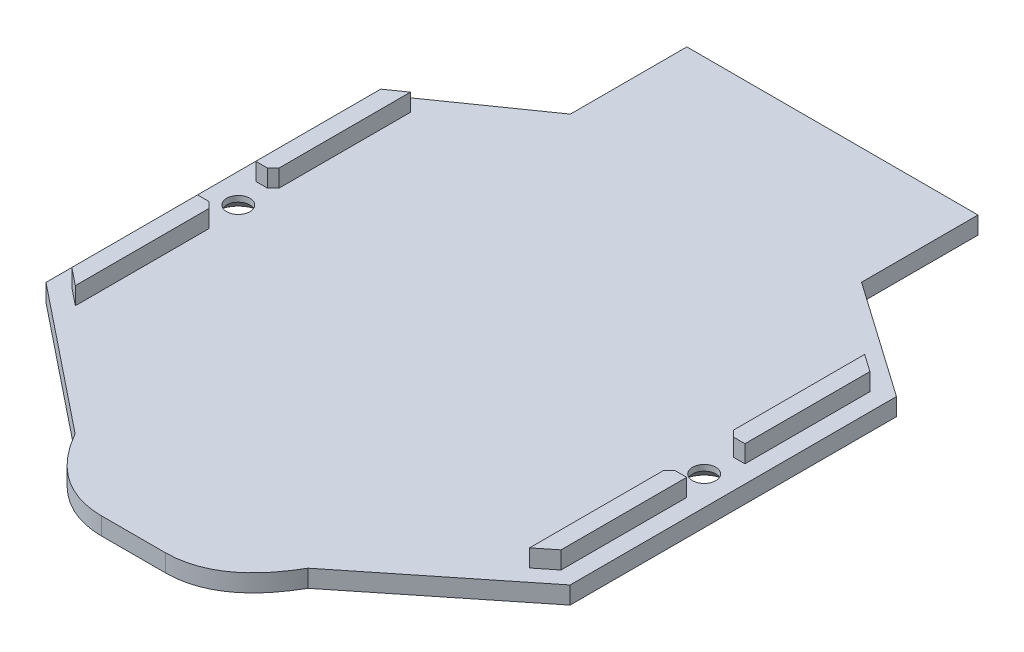
SolidWorks part; units mm, degrees
ref_plane "Front Plane" through (0, 0, 0) normal (0, 0, 1) x (1, 0, 0)
ref_plane "Top Plane" through (0, 0, 0) normal (0, 1, 0) x (1, 0, 0)
ref_plane "Right Plane" through (0, 0, 0) normal (1, 0, 0) x (0, 0, -1)
sketch "Sketch1" plane through (0, 0, 0) normal (0, 1, 0) x (1, 0, 0)
  line L0 (16.2204, 37.1807) -> (14.3154, 37.1807)
  line L1 (14.3154, 37.1807) -> (14.3154, 23.4889)
  line L2 (14.3154, 23.4889) -> (27.0154, 14.5989)
  line L3 (27.0154, 14.5989) -> (27.0154, 0.9716)
  line L4 (27.0154, 0.9716) -> (25.7454, 0.9716)
  line L5 (25.7454, -5.3784) -> (27.0154, -5.3784)
  line L6 (27.0154, -5.3784) -> (27.0154, -19.0819)
  line L7 (27.0154, -19.0819) -> (11.5652, -31.4422)
  line L8 (3.8247, -37.1143) -> (-3.1264, -37.1143)
  line L9 (-10.8743, -31.4422) -> (-26.3246, -19.0819)
  line L10 (-26.3246, -19.0819) -> (-26.3246, -5.3784)
  line L11 (-26.3246, -5.3784) -> (-25.0546, -5.3784)
  line L12 (-25.0546, 0.9716) -> (-26.3246, 0.9716)
  line L13 (-26.3246, 0.9716) -> (-26.3246, 14.5989)
  line L14 (-26.3246, 14.5989) -> (-13.6246, 23.4889)
  line L15 (-13.6246, 23.4889) -> (-13.6246, 37.1807)
  line L16 (-13.6246, 37.1807) -> (-15.5296, 37.1807)
  line L17 (-15.5296, 37.1807) -> (-15.5296, 24.4807)
  line L18 (-15.5296, 24.4807) -> (-28.2296, 15.5907)
  line L19 (-28.2296, 15.5907) -> (-28.2296, -19.9975)
  line L20 (-28.2296, -19.9975) -> (-12.3546, -32.6975)
  line L21 (-3.1338, -39.0193) -> (3.8247, -39.0193)
  line L22 (13.0454, -32.6975) -> (28.9204, -19.9975)
  line L23 (28.9204, -19.9975) -> (28.9204, 15.5907)
  line L24 (28.9204, 15.5907) -> (16.2204, 24.4807)
  line L25 (16.2204, 24.4807) -> (16.2204, 37.1807)
  line L26 (-15.5296, 37.1807) -> (16.2204, 37.1807)
  arc A0 (25.7454, 0.9716) -> (25.7454, -5.3784) centre (25.7454, -2.2034) ccw
  arc A1 (-25.0546, -5.3784) -> (-25.0546, 0.9716) centre (-25.0546, -2.2034) ccw
  spline S0 degree 3 poles (11.5652, -31.4422) (11.1586, -32.1832) (10.712, -32.8933) (9.9543, -33.8908) (9.687, -34.2118) (9.1149, -34.8251) (8.8087, -35.1186) (8.1538, -35.6622) (7.8103, -35.908) (7.267, -36.2313) (7.0812, -36.3315) (6.6996, -36.5157) (6.5025, -36.5999) (5.5058, -36.9719) (4.6781, -37.1102) (3.8247, -37.1143) knots 0 0 0 0 0.25 0.25 0.375 0.375 0.5 0.5 0.625 0.625 0.6875 0.6875 0.75 0.75 1 1 1 1
  spline S1 degree 3 poles (-3.1264, -37.1143) (-3.9804, -37.111) (-4.8089, -36.9733) (-5.8065, -36.602) (-6.0037, -36.5178) (-6.3858, -36.3339) (-6.5718, -36.2337) (-7.1158, -35.9104) (-7.4596, -35.6646) (-8.1153, -35.121) (-8.4218, -34.8273) (-8.9945, -34.2137) (-9.2621, -33.8925) (-10.0205, -32.8944) (-10.4674, -32.1837) (-10.8743, -31.4422) knots 0 0 0 0 0.25 0.25 0.3125 0.3125 0.375 0.375 0.5 0.5 0.625 0.625 0.75 0.75 1 1 1 1
  spline S2 degree 3 poles (-12.3546, -32.6975) (-10.3573, -36.1919) (-7.4671, -39.0025) (-3.1338, -39.0193) knots 0.450644 0.450644 0.450644 0.450644 1 1 1 1
  spline S3 degree 3 poles (3.8247, -39.0193) (8.158, -39.0025) (11.0482, -36.1919) (13.0454, -32.6975) knots 0.450644 0.450644 0.450644 0.450644 1 1 1 1
sketch "Sketch2" plane through (0, 0, 0) normal (0, 1, 0) x (1, 0, 0)
  line L0 (-28.2296, 15.5907) -> (-28.2296, -19.9975) construction
  line L1 (-15.5296, 24.4807) -> (-28.2296, 15.5907) construction
  line L2 (-15.5296, 37.1807) -> (-15.5296, 24.4807) construction
  line L3 (-15.5296, 37.1807) -> (16.2204, 37.1807) construction
  line L4 (16.2204, 24.4807) -> (16.2204, 37.1807) construction
  line L5 (28.9204, 15.5907) -> (16.2204, 24.4807) construction
  line L6 (28.9204, -19.9975) -> (28.9204, 15.5907) construction
  line L7 (13.0454, -32.6975) -> (28.9204, -19.9975) construction
  line L8 (-3.1338, -39.0193) -> (3.8247, -39.0193) construction
  line L9 (-28.2296, -19.9975) -> (-12.3546, -32.6975) construction
  line L10 (-28.2296, 15.5907) -> (-28.2296, -19.9975)
  line L11 (-15.5296, 24.4807) -> (-28.2296, 15.5907)
  line L12 (-15.5296, 37.1807) -> (-15.5296, 24.4807)
  line L13 (-15.5296, 37.1807) -> (16.2204, 37.1807)
  line L14 (16.2204, 24.4807) -> (16.2204, 37.1807)
  line L15 (28.9204, 15.5907) -> (16.2204, 24.4807)
  line L16 (28.9204, -19.9975) -> (28.9204, 15.5907)
  line L17 (13.0454, -32.6975) -> (28.9204, -19.9975)
  line L18 (-3.1338, -39.0193) -> (3.8247, -39.0193)
  line L19 (-28.2296, -19.9975) -> (-12.3546, -32.6975)
  spline S0 degree 3 poles (-1372.2239, 3712.8512) (1134.3547, -4013.4655) (-902.3208, 4019.2005) (797.1704, -3954.7495) knots -5.551331 -5.551331 -5.551331 -5.551331 8.013046 8.013046 8.013046 8.013046 only from (3.8247, -39.0193) to (13.0454, -32.6975) construction
  spline S1 degree 3 poles (-601.8963, -3989.0758) (204.2826, 518.7984) (43.0145, -54.773) (-5.8065, -36.602) (-6.0037, -36.5178) (-6.3858, -36.3339) (-6.5718, -36.2337) (-7.1158, -35.9104) (-7.4596, -35.6646) (-8.1153, -35.121) (-8.4218, -34.8273) (-8.9945, -34.2137) (-9.2621, -33.8925) (-39.1665, 5.4647) (132.9955, 200.2639) (-3261.6051, -2358.0304) knots -14.980553 -14.980553 -14.980553 -14.980553 0.25 0.25 0.3125 0.3125 0.375 0.375 0.5 0.5 0.625 0.625 0.75 0.75 15.412318 15.412318 15.412318 15.412318 only from (-3.1264, -37.1143) to (-10.8743, -31.4422) construction
  spline S2 degree 3 poles (-796.4893, -3954.7951) (903.0253, 4019.2584) (-1133.6825, -4013.5351) (1372.9405, 3712.9303) knots -6.562429 -6.562429 -6.562429 -6.562429 7.002021 7.002021 7.002021 7.002021 only from (-12.3546, -32.6975) to (-3.1338, -39.0193) construction
  spline S3 degree 3 poles (3.8247, -39.0193) (8.158, -39.0025) (11.0482, -36.1919) (13.0454, -32.6975) knots 0.450644 0.450644 0.450644 0.450644 1 1 1 1
  spline S4 degree 3 poles (-3.1264, -37.1143) (-3.9804, -37.111) (-4.8089, -36.9733) (-5.8065, -36.602) (-6.0037, -36.5178) (-6.3858, -36.3339) (-6.5718, -36.2337) (-7.1158, -35.9104) (-7.4596, -35.6646) (-8.1153, -35.121) (-8.4218, -34.8273) (-8.9945, -34.2137) (-9.2621, -33.8925) (-10.0205, -32.8944) (-10.4674, -32.1837) (-10.8743, -31.4422) knots 0 0 0 0 0.25 0.25 0.3125 0.3125 0.375 0.375 0.5 0.5 0.625 0.625 0.75 0.75 1 1 1 1
  spline S5 degree 3 poles (-12.3546, -32.6975) (-10.3573, -36.1919) (-7.4671, -39.0025) (-3.1338, -39.0193) knots 0.450644 0.450644 0.450644 0.450644 1 1 1 1
extrude "Boss-Extrude1" add sketch "Sketch2" along normal blind 1.905
sketch "Sketch3" plane through (0, 0, 0) normal (0, 1, 0) x (1, 0, 0)
  line L0 (-13.6246, 37.1807) -> (-15.5296, 37.1807) construction
  line L1 (-13.6246, 23.4889) -> (-13.6246, 37.1807) construction
  line L2 (-26.3246, 14.5989) -> (-13.6246, 23.4889) construction
  line L3 (-26.3246, 0.9716) -> (-26.3246, 14.5989) construction
  line L4 (-25.0546, 0.9716) -> (-26.3246, 0.9716) construction
  line L5 (-26.3246, -5.3784) -> (-25.0546, -5.3784) construction
  line L6 (-26.3246, -19.0819) -> (-26.3246, -5.3784) construction
  line L7 (-10.8743, -31.4422) -> (-26.3246, -19.0819) construction
  line L8 (3.8247, -37.1143) -> (-3.1264, -37.1143) construction
  line L9 (27.0154, -19.0819) -> (11.5652, -31.4422) construction
  line L10 (27.0154, -5.3784) -> (27.0154, -19.0819) construction
  line L11 (25.7454, -5.3784) -> (27.0154, -5.3784) construction
  line L12 (27.0154, 0.9716) -> (25.7454, 0.9716) construction
  line L13 (27.0154, 14.5989) -> (27.0154, 0.9716) construction
  line L14 (14.3154, 23.4889) -> (27.0154, 14.5989) construction
  line L15 (14.3154, 37.1807) -> (14.3154, 23.4889) construction
  line L16 (16.2204, 37.1807) -> (14.3154, 37.1807) construction
  line L17 (-15.5296, 37.1807) -> (-15.5296, 24.4807) construction
  line L18 (-15.5296, 24.4807) -> (-28.2296, 15.5907) construction
  line L19 (-28.2296, 15.5907) -> (-28.2296, -19.9975) construction
  line L20 (-28.2296, -19.9975) -> (-12.3546, -32.6975) construction
  line L21 (-3.1338, -39.0193) -> (3.8247, -39.0193) construction
  line L22 (13.0454, -32.6975) -> (28.9204, -19.9975) construction
  line L23 (28.9204, -19.9975) -> (28.9204, 15.5907) construction
  line L24 (28.9204, 15.5907) -> (16.2204, 24.4807) construction
  line L25 (16.2204, 24.4807) -> (16.2204, 37.1807) construction
  line L26 (-15.5296, 37.1807) -> (16.2204, 37.1807) construction
  line L27 (-13.6246, 37.1807) -> (-15.5296, 37.1807)
  line L28 (-13.6246, 23.4889) -> (-13.6246, 37.1807)
  line L29 (-26.3246, 14.5989) -> (-13.6246, 23.4889)
  line L30 (-26.3246, 0.9716) -> (-26.3246, 14.5989)
  line L31 (-25.0546, 0.9716) -> (-26.3246, 0.9716)
  line L32 (-26.3246, -5.3784) -> (-25.0546, -5.3784)
  line L33 (-26.3246, -19.0819) -> (-26.3246, -5.3784)
  line L34 (-10.8743, -31.4422) -> (-26.3246, -19.0819)
  line L35 (3.8247, -37.1143) -> (-3.1264, -37.1143)
  line L36 (27.0154, -19.0819) -> (11.5652, -31.4422)
  line L37 (27.0154, -5.3784) -> (27.0154, -19.0819)
  line L38 (25.7454, -5.3784) -> (27.0154, -5.3784)
  line L39 (27.0154, 0.9716) -> (25.7454, 0.9716)
  line L40 (27.0154, 14.5989) -> (27.0154, 0.9716)
  line L41 (14.3154, 23.4889) -> (27.0154, 14.5989)
  line L42 (14.3154, 37.1807) -> (14.3154, 23.4889)
  line L43 (16.2204, 37.1807) -> (14.3154, 37.1807)
  line L44 (-15.5296, 37.1807) -> (-15.5296, 24.4807)
  line L45 (-15.5296, 24.4807) -> (-28.2296, 15.5907)
  line L46 (-28.2296, 15.5907) -> (-28.2296, -19.9975)
  line L47 (-28.2296, -19.9975) -> (-12.3546, -32.6975)
  line L48 (-3.1338, -39.0193) -> (3.8247, -39.0193)
  line L49 (13.0454, -32.6975) -> (28.9204, -19.9975)
  line L50 (28.9204, -19.9975) -> (28.9204, 15.5907)
  line L51 (28.9204, 15.5907) -> (16.2204, 24.4807)
  line L52 (16.2204, 24.4807) -> (16.2204, 37.1807)
  line L53 (-15.5296, 37.1807) -> (16.2204, 37.1807)
  line L54 (-25.0546, 0.9716) -> (-24.4196, 1.6066)
  line L55 (-24.4196, 1.6066) -> (-24.4196, 15.9324)
  line L56 (-25.0546, -5.3784) -> (-24.4196, -6.0134)
  line L57 (-24.4196, -6.0134) -> (-24.4196, -20.6059)
  line L58 (0.3454, 37.1807) -> (0.3454, -39.0193) construction
  line L59 (25.1104, -6.0134) -> (25.1104, -20.6059)
  line L60 (25.7454, -5.3784) -> (25.1104, -6.0134)
  line L61 (25.1104, 1.6066) -> (25.1104, 15.9324)
  line L62 (25.7454, 0.9716) -> (25.1104, 1.6066)
  line L63 (28.9204, 15.5907) -> (28.9204, -19.9975)
  line L64 (16.2204, 24.4807) -> (28.9204, 15.5907)
  line L65 (27.0154, -19.0819) -> (27.0154, -5.3784)
  line L66 (27.0154, -5.3784) -> (25.7454, -5.3784)
  line L67 (25.7454, 0.9716) -> (27.0154, 0.9716)
  line L68 (27.0154, 0.9716) -> (27.0154, 14.5989)
  line L69 (27.0154, 14.5989) -> (14.3154, 23.4889)
  arc A0 (-25.0546, -5.3784) -> (-25.0546, 0.9716) centre (-25.0546, -2.2034) ccw construction
  arc A1 (25.7454, 0.9716) -> (25.7454, -5.3784) centre (25.7454, -2.2034) ccw construction
  arc A2 (-25.0546, -5.3784) -> (-25.0546, 0.9716) centre (-25.0546, -2.2034) ccw
  arc A3 (25.7454, 0.9716) -> (25.7454, -5.3784) centre (25.7454, -2.2034) ccw
  arc A4 (25.7454, -5.3784) -> (25.7454, 0.9716) centre (25.7454, -2.2034) cw
  spline S0 degree 3 poles (-426.9181, -3004.5813) (179.2751, 431.0709) (39.1367, -53.3297) (-5.8065, -36.602) (-6.0037, -36.5178) (-6.3858, -36.3339) (-6.5718, -36.2337) (-7.1158, -35.9104) (-7.4596, -35.6646) (-8.1153, -35.121) (-8.4218, -34.8273) (-8.9945, -34.2137) (-9.2621, -33.8925) (-36.616, 2.108) (104.8717, 167.9052) (-2462.4158, -1757.1324) knots -13.76583 -13.76583 -13.76583 -13.76583 0.25 0.25 0.3125 0.3125 0.375 0.375 0.5 0.5 0.625 0.625 0.75 0.75 14.151142 14.151142 14.151142 14.151142 only from (-3.1264, -37.1143) to (-10.8743, -31.4422) construction
  spline S1 degree 3 poles (2463.1832, -1757.169) (-104.1653, 167.9053) (37.3056, 2.1164) (9.9543, -33.8908) (9.687, -34.2118) (9.1149, -34.8251) (8.8087, -35.1186) (8.1538, -35.6622) (7.8103, -35.908) (7.267, -36.2313) (7.0812, -36.3315) (6.6996, -36.5157) (6.5025, -36.5999) (-38.502, -53.3933) (-179.2821, 432.5621) (428.9356, -3004.4043) knots -13.162322 -13.162322 -13.162322 -13.162322 0.25 0.25 0.375 0.375 0.5 0.5 0.625 0.625 0.6875 0.6875 0.75 0.75 14.797872 14.797872 14.797872 14.797872 only from (11.5652, -31.4422) to (3.8247, -37.1143) construction
  spline S2 degree 3 poles (-589.7865, -2976.415) (667.4627, 3033.8674) (-863.1992, -3037.4657) (1061.4, 2762.7226) knots -5.954611 -5.954611 -5.954611 -5.954611 6.391637 6.391637 6.391637 6.391637 only from (-12.3546, -32.6975) to (-3.1338, -39.0193) construction
  spline S3 degree 3 poles (-1060.6911, 2762.6682) (863.8771, -3037.4176) (-666.7625, 3033.8272) (590.4708, -2976.3833) knots -4.940954 -4.940954 -4.940954 -4.940954 7.405233 7.405233 7.405233 7.405233 only from (3.8247, -39.0193) to (13.0454, -32.6975) construction
  spline S4 degree 3 poles (-3.1264, -37.1143) (-3.9804, -37.111) (-4.8089, -36.9733) (-5.8065, -36.602) (-6.0037, -36.5178) (-6.3858, -36.3339) (-6.5718, -36.2337) (-7.1158, -35.9104) (-7.4596, -35.6646) (-8.1153, -35.121) (-8.4218, -34.8273) (-8.9945, -34.2137) (-9.2621, -33.8925) (-10.0205, -32.8944) (-10.4674, -32.1837) (-10.8743, -31.4422) knots 0 0 0 0 0.25 0.25 0.3125 0.3125 0.375 0.375 0.5 0.5 0.625 0.625 0.75 0.75 1 1 1 1
  spline S5 degree 3 poles (11.5652, -31.4422) (11.1586, -32.1832) (10.712, -32.8933) (9.9543, -33.8908) (9.687, -34.2118) (9.1149, -34.8251) (8.8087, -35.1186) (8.1538, -35.6622) (7.8103, -35.908) (7.267, -36.2313) (7.0812, -36.3315) (6.6996, -36.5157) (6.5025, -36.5999) (5.5058, -36.9719) (4.6781, -37.1102) (3.8247, -37.1143) knots 0 0 0 0 0.25 0.25 0.375 0.375 0.5 0.5 0.625 0.625 0.6875 0.6875 0.75 0.75 1 1 1 1
  spline S6 degree 3 poles (-12.3546, -32.6975) (-10.3573, -36.1919) (-7.4671, -39.0025) (-3.1338, -39.0193) knots 0.450644 0.450644 0.450644 0.450644 1 1 1 1
  spline S7 degree 3 poles (3.8247, -39.0193) (8.158, -39.0025) (11.0482, -36.1919) (13.0454, -32.6975) knots 0.450644 0.450644 0.450644 0.450644 1 1 1 1
  dimension "D1" = 135
  dimension "D2" = 135
  dimension "D3" = 1.905
  dimension "D4" = 1.905
extrude "Boss-Extrude2" add sketch "Sketch3" along normal blind 3.81 contours L54 L55 L29 L30 L31 | L57 L56 L32 L33 L34 | L62 L39 L40 L41 L61 | L38 L60 L59 L36 L37
sketch "Sketch4" plane through (0, 0, 0) normal (0, 1, 0) x (1, 0, 0)
  line L0 (-13.6246, 37.1807) -> (-15.5296, 37.1807) construction
  line L1 (-13.6246, 23.4889) -> (-13.6246, 37.1807) construction
  line L2 (-26.3246, 14.5989) -> (-13.6246, 23.4889) construction
  line L3 (-26.3246, 0.9716) -> (-26.3246, 14.5989) construction
  line L4 (-25.0546, 0.9716) -> (-26.3246, 0.9716) construction
  line L5 (-26.3246, -5.3784) -> (-25.0546, -5.3784) construction
  line L6 (-26.3246, -19.0819) -> (-26.3246, -5.3784) construction
  line L7 (-10.8743, -31.4422) -> (-26.3246, -19.0819) construction
  line L8 (3.8247, -37.1143) -> (-3.1264, -37.1143) construction
  line L9 (27.0154, -19.0819) -> (11.5652, -31.4422) construction
  line L10 (27.0154, -5.3784) -> (27.0154, -19.0819) construction
  line L11 (25.7454, -5.3784) -> (27.0154, -5.3784) construction
  line L12 (27.0154, 0.9716) -> (25.7454, 0.9716) construction
  line L13 (27.0154, 14.5989) -> (27.0154, 0.9716) construction
  line L14 (14.3154, 23.4889) -> (27.0154, 14.5989) construction
  line L15 (14.3154, 37.1807) -> (14.3154, 23.4889) construction
  line L16 (16.2204, 37.1807) -> (14.3154, 37.1807) construction
  line L17 (-15.5296, 37.1807) -> (-15.5296, 24.4807) construction
  line L18 (-15.5296, 24.4807) -> (-28.2296, 15.5907) construction
  line L19 (-28.2296, 15.5907) -> (-28.2296, -19.9975) construction
  line L20 (-28.2296, -19.9975) -> (-12.3546, -32.6975) construction
  line L21 (-3.1338, -39.0193) -> (3.8247, -39.0193) construction
  line L22 (13.0454, -32.6975) -> (28.9204, -19.9975) construction
  line L23 (28.9204, -19.9975) -> (28.9204, 15.5907) construction
  line L24 (28.9204, 15.5907) -> (16.2204, 24.4807) construction
  line L25 (16.2204, 24.4807) -> (16.2204, 37.1807) construction
  line L26 (-15.5296, 37.1807) -> (16.2204, 37.1807) construction
  line L27 (-13.6246, 37.1807) -> (-15.5296, 37.1807)
  line L28 (-13.6246, 23.4889) -> (-13.6246, 37.1807)
  line L29 (-26.3246, 14.5989) -> (-13.6246, 23.4889)
  line L30 (-26.3246, 0.9716) -> (-26.3246, 14.5989)
  line L31 (-25.0546, 0.9716) -> (-26.3246, 0.9716)
  line L32 (-26.3246, -5.3784) -> (-25.0546, -5.3784)
  line L33 (-26.3246, -19.0819) -> (-26.3246, -5.3784)
  line L34 (-10.8743, -31.4422) -> (-26.3246, -19.0819)
  line L35 (3.8247, -37.1143) -> (-3.1264, -37.1143)
  line L36 (27.0154, -19.0819) -> (11.5652, -31.4422)
  line L37 (27.0154, -5.3784) -> (27.0154, -19.0819)
  line L38 (25.7454, -5.3784) -> (27.0154, -5.3784)
  line L39 (27.0154, 0.9716) -> (25.7454, 0.9716)
  line L40 (27.0154, 14.5989) -> (27.0154, 0.9716)
  line L41 (14.3154, 23.4889) -> (27.0154, 14.5989)
  line L42 (14.3154, 37.1807) -> (14.3154, 23.4889)
  line L43 (16.2204, 37.1807) -> (14.3154, 37.1807)
  line L44 (-15.5296, 37.1807) -> (-15.5296, 24.4807)
  line L45 (-15.5296, 24.4807) -> (-28.2296, 15.5907)
  line L46 (-28.2296, 15.5907) -> (-28.2296, -19.9975)
  line L47 (-28.2296, -19.9975) -> (-12.3546, -32.6975)
  line L48 (-3.1338, -39.0193) -> (3.8247, -39.0193)
  line L49 (13.0454, -32.6975) -> (28.9204, -19.9975)
  line L50 (28.9204, -19.9975) -> (28.9204, 15.5907)
  line L51 (28.9204, 15.5907) -> (16.2204, 24.4807)
  line L52 (16.2204, 24.4807) -> (16.2204, 37.1807)
  line L53 (-15.5296, 37.1807) -> (16.2204, 37.1807)
  arc A0 (-25.0546, -5.3784) -> (-25.0546, 0.9716) centre (-25.0546, -2.2034) ccw construction
  arc A1 (25.7454, 0.9716) -> (25.7454, -5.3784) centre (25.7454, -2.2034) ccw construction
  arc A2 (-25.0546, -5.3784) -> (-25.0546, 0.9716) centre (-25.0546, -2.2034) ccw
  arc A3 (25.7454, 0.9716) -> (25.7454, -5.3784) centre (25.7454, -2.2034) ccw
  circle A4 centre (-25.0546, -2.2034) radius 1.27
  circle A5 centre (25.7454, -2.2034) radius 1.27
  spline S0 degree 3 poles (-426.9181, -3004.5813) (179.2751, 431.0709) (39.1367, -53.3297) (-5.8065, -36.602) (-6.0037, -36.5178) (-6.3858, -36.3339) (-6.5718, -36.2337) (-7.1158, -35.9104) (-7.4596, -35.6646) (-8.1153, -35.121) (-8.4218, -34.8273) (-8.9945, -34.2137) (-9.2621, -33.8925) (-36.616, 2.108) (104.8717, 167.9052) (-2462.4158, -1757.1324) knots -13.76583 -13.76583 -13.76583 -13.76583 0.25 0.25 0.3125 0.3125 0.375 0.375 0.5 0.5 0.625 0.625 0.75 0.75 14.151142 14.151142 14.151142 14.151142 only from (-3.1264, -37.1143) to (-10.8743, -31.4422) construction
  spline S1 degree 3 poles (2463.1832, -1757.169) (-104.1653, 167.9053) (37.3056, 2.1164) (9.9543, -33.8908) (9.687, -34.2118) (9.1149, -34.8251) (8.8087, -35.1186) (8.1538, -35.6622) (7.8103, -35.908) (7.267, -36.2313) (7.0812, -36.3315) (6.6996, -36.5157) (6.5025, -36.5999) (-38.502, -53.3933) (-179.2821, 432.5621) (428.9356, -3004.4043) knots -13.162322 -13.162322 -13.162322 -13.162322 0.25 0.25 0.375 0.375 0.5 0.5 0.625 0.625 0.6875 0.6875 0.75 0.75 14.797872 14.797872 14.797872 14.797872 only from (11.5652, -31.4422) to (3.8247, -37.1143) construction
  spline S2 degree 3 poles (-589.7865, -2976.415) (667.4627, 3033.8674) (-863.1992, -3037.4657) (1061.4, 2762.7226) knots -5.954611 -5.954611 -5.954611 -5.954611 6.391637 6.391637 6.391637 6.391637 only from (-12.3546, -32.6975) to (-3.1338, -39.0193) construction
  spline S3 degree 3 poles (-1060.6911, 2762.6682) (863.8771, -3037.4176) (-666.7625, 3033.8272) (590.4708, -2976.3833) knots -4.940954 -4.940954 -4.940954 -4.940954 7.405233 7.405233 7.405233 7.405233 only from (3.8247, -39.0193) to (13.0454, -32.6975) construction
  spline S4 degree 3 poles (-3.1264, -37.1143) (-3.9804, -37.111) (-4.8089, -36.9733) (-5.8065, -36.602) (-6.0037, -36.5178) (-6.3858, -36.3339) (-6.5718, -36.2337) (-7.1158, -35.9104) (-7.4596, -35.6646) (-8.1153, -35.121) (-8.4218, -34.8273) (-8.9945, -34.2137) (-9.2621, -33.8925) (-10.0205, -32.8944) (-10.4674, -32.1837) (-10.8743, -31.4422) knots 0 0 0 0 0.25 0.25 0.3125 0.3125 0.375 0.375 0.5 0.5 0.625 0.625 0.75 0.75 1 1 1 1
  spline S5 degree 3 poles (11.5652, -31.4422) (11.1586, -32.1832) (10.712, -32.8933) (9.9543, -33.8908) (9.687, -34.2118) (9.1149, -34.8251) (8.8087, -35.1186) (8.1538, -35.6622) (7.8103, -35.908) (7.267, -36.2313) (7.0812, -36.3315) (6.6996, -36.5157) (6.5025, -36.5999) (5.5058, -36.9719) (4.6781, -37.1102) (3.8247, -37.1143) knots 0 0 0 0 0.25 0.25 0.375 0.375 0.5 0.5 0.625 0.625 0.6875 0.6875 0.75 0.75 1 1 1 1
  spline S6 degree 3 poles (-12.3546, -32.6975) (-10.3573, -36.1919) (-7.4671, -39.0025) (-3.1338, -39.0193) knots 0.450644 0.450644 0.450644 0.450644 1 1 1 1
  spline S7 degree 3 poles (3.8247, -39.0193) (8.158, -39.0025) (11.0482, -36.1919) (13.0454, -32.6975) knots 0.450644 0.450644 0.450644 0.450644 1 1 1 1
  dimension "D1" = 2.54
extrude "Cut-Extrude1" cut sketch "Sketch4" along normal blind 3.81 contours A4 | A5
chamfer "Chamfer1" distance 1.27 angle 45 2 edges at (-25.0546, 0, 3.4734) (25.7454, 0, 3.4734)
sketch "Sketch5" plane through (0, 0, 0) normal (0, -1, 0) x (1, 0, 0)
  line L0 (-6.6396, 25.4) -> (7.3304, 25.4) construction
  line L1 (-6.6396, 26.9875) -> (7.3304, 26.9875)
  line L2 (-6.6396, 23.8125) -> (7.3304, 23.8125)
  line L3 (-6.6396, -30.48) -> (7.3304, -30.48) construction
  line L4 (-6.6396, -28.8925) -> (7.3304, -28.8925)
  line L5 (-6.6396, -32.0675) -> (7.3304, -32.0675)
  line L6 (-18.7046, 17.1118) -> (-18.7046, 10.1268) construction
  line L7 (-17.1171, 17.1118) -> (-17.1171, 10.1268)
  line L8 (-20.2921, 17.1118) -> (-20.2921, 10.1268)
  line L9 (19.3954, 17.1118) -> (19.3954, 10.1268) construction
  line L10 (20.9829, 17.1118) -> (20.9829, 10.1268)
  line L11 (17.8079, 17.1118) -> (17.8079, 10.1268)
  line L13 (0.3454, 39.0193) -> (0.3454, -37.1807) construction
  line L14 (-3.1338, 39.0193) -> (3.8247, 39.0193) construction
  line L15 (-15.5296, -37.1807) -> (16.2204, -37.1807) construction
  arc A0 (-6.6396, 26.9875) -> (-6.6396, 23.8125) centre (-6.6396, 25.4) ccw
  arc A1 (7.3304, 23.8125) -> (7.3304, 26.9875) centre (7.3304, 25.4) ccw
  arc A2 (-6.6396, -28.8925) -> (-6.6396, -32.0675) centre (-6.6396, -30.48) ccw
  arc A3 (7.3304, -32.0675) -> (7.3304, -28.8925) centre (7.3304, -30.48) ccw
  arc A4 (-17.1171, 17.1118) -> (-20.2921, 17.1118) centre (-18.7046, 17.1118) ccw
  arc A5 (-20.2921, 10.1268) -> (-17.1171, 10.1268) centre (-18.7046, 10.1268) ccw
  arc A6 (20.9829, 17.1118) -> (17.8079, 17.1118) centre (19.3954, 17.1118) ccw
  arc A7 (17.8079, 10.1268) -> (20.9829, 10.1268) centre (19.3954, 10.1268) ccw
  point P2 (0.3454, 25.4)
  point P7 (0.3454, -30.48)
  point P14 (-18.7046, 13.6193)
  point P21 (19.3954, 13.6193)
  dimension "D1" = 3.175
  dimension "D2" = 25.4
  dimension "D3" = 30.48
  dimension "D4" = 19.05
  dimension "D5" = 19.05
  dimension "D6" = 25.4
  dimension "D7" = 25.4
  dimension "D8" = 3.175
  dimension "D9" = 3.175
  dimension "D10" = 3.175
  dimension "D11" = 6.985
  dimension "D12" = 6.985
  dimension "D13" = 13.97
  dimension "D14" = 13.97
extrude "Boss-Extrude3" add sketch "Sketch5" along normal blind 1.905
